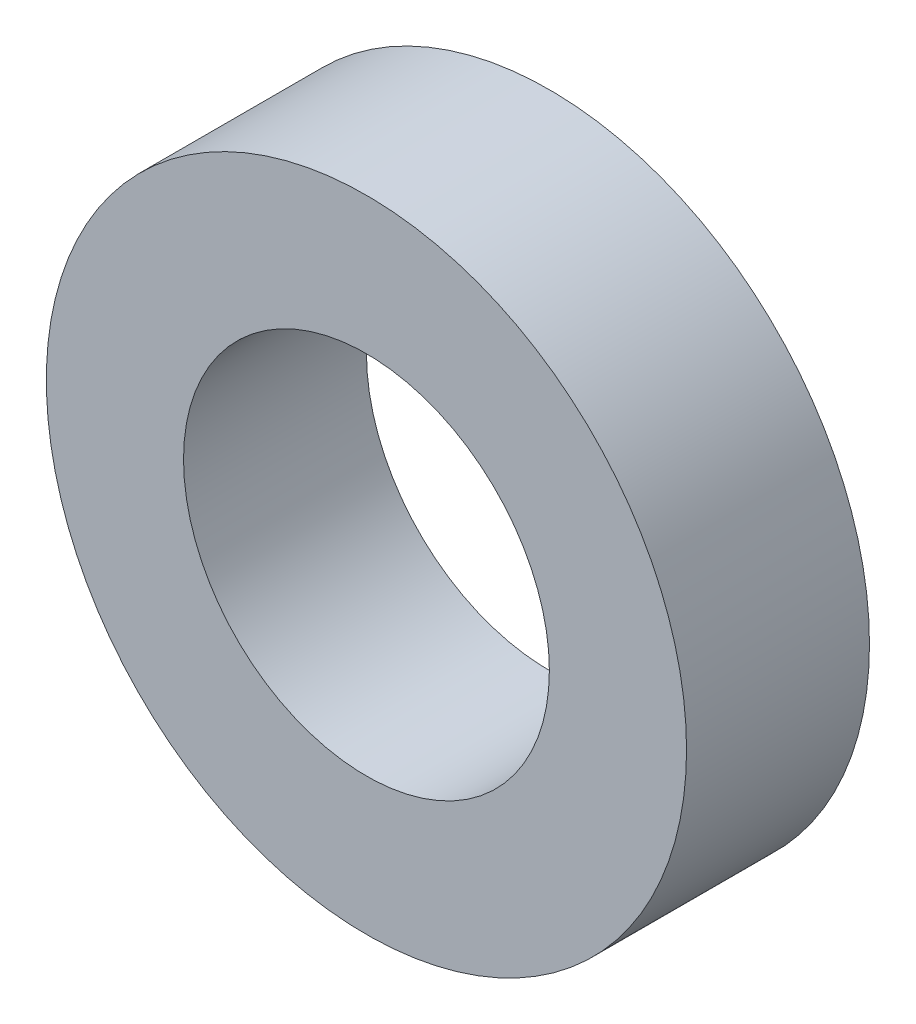
SolidWorks part; units mm, degrees
material "Nylon 101"
ref_plane "Front Plane" through (0, 0, 0) normal (0, 0, 1) x (1, 0, 0)
ref_plane "Top Plane" through (0, 0, 0) normal (0, 1, 0) x (1, 0, 0)
ref_plane "Right Plane" through (0, 0, 0) normal (1, 0, 0) x (0, 0, -1)
sketch "Sketch1" plane through (0, 0, 0) normal (0, 0, 1) x (1, 0, 0)
  circle A0 centre (0, 0) radius 6.35
  circle A1 centre (0, 0) radius 11.1125
  dimension "D1" = 12.7
  dimension "D2" = 22.225
extrude "Boss-Extrude1" add sketch "Sketch1" along normal mid plane 6.35
